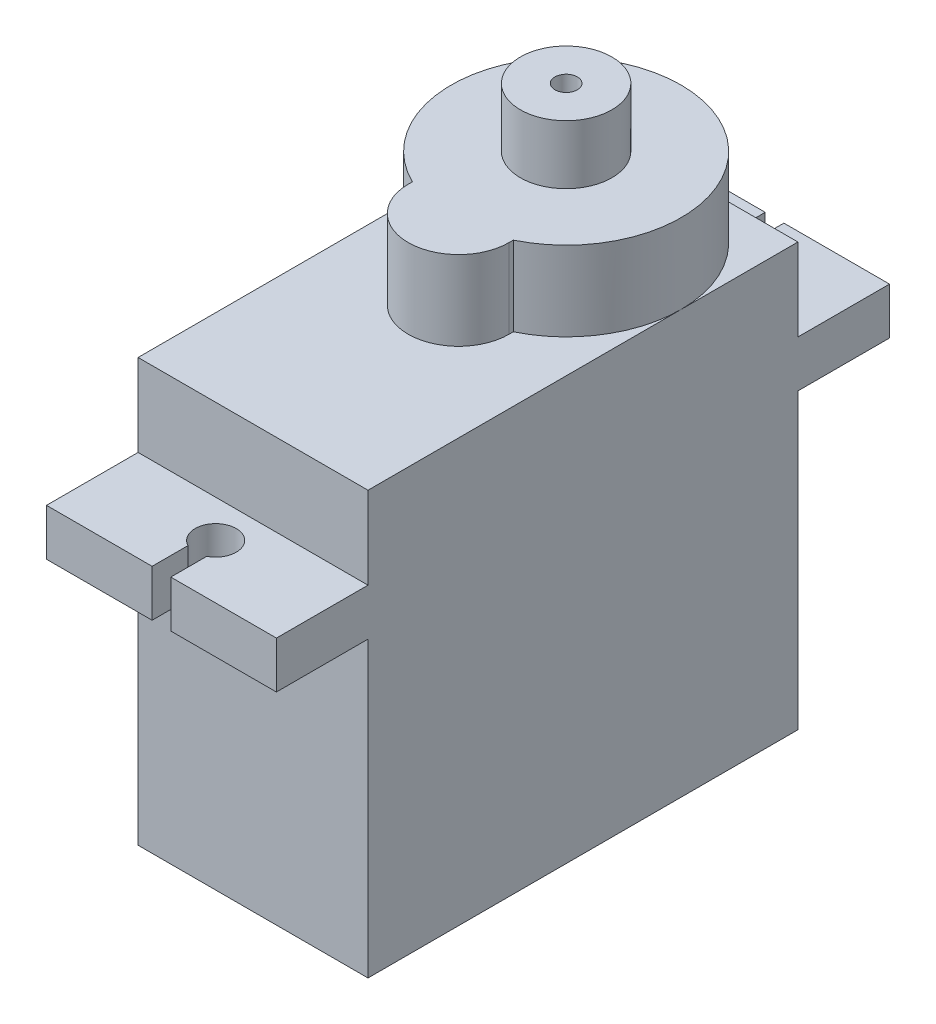
SolidWorks part; units mm, degrees
ref_plane "Ön Düzlem" through (0, 0, 0) normal (0, 0, 1) x (1, 0, 0)
ref_plane "Üst Düzlem" through (0, 0, 0) normal (0, 1, 0) x (1, 0, 0)
ref_plane "Sağ Düzlem" through (0, 0, 0) normal (1, 0, 0) x (0, 0, -1)
sketch "Çizim1" plane through (0, 0, 0) normal (0, 1, 0) x (1, 0, 0)
  line L1 (-6.15, -11.5) -> (6.15, -11.5)
  line L2 (-6.15, -11.5) -> (-6.15, 11.5)
  line L3 (-6.15, 11.5) -> (6.15, 11.5)
  line L4 (6.15, -11.5) -> (6.15, 11.5)
  line L5 (-6.15, -11.5) -> (6.15, 11.5) construction
  line L6 (-6.15, 11.5) -> (6.15, -11.5) construction
  point P0 (0, 0)
  dimension "D1" = 12.3
  dimension "D2" = 23
extrude "Yükseklik-Ekstrüzyon1" add sketch "Çizim1" along normal blind 22.6
ref_plane "Düzlem1" through (0, 18.2, 0) normal (0, 1, 0) x (1, 0, 0)
sketch "Çizim2" plane through (0, 18.2, 0) normal (0, 1, 0) x (1, 0, 0)
  line L0 (6.15, -11.5) -> (6.15, 11.5) construction
  line L1 (-6.15, -16.4) -> (6.15, -16.4)
  line L2 (-6.15, -16.4) -> (-6.15, 16.4)
  line L3 (-6.15, 16.4) -> (6.15, 16.4)
  line L4 (6.15, -16.4) -> (6.15, 16.4)
  line L5 (-6.15, -16.4) -> (6.15, 16.4) construction
  line L6 (-6.15, 16.4) -> (6.15, -16.4) construction
  line L7 (0, 13.5) -> (0, 16.4) construction
  line L8 (0.5, 14.4798) -> (0.5, 16.4)
  line L9 (-0.5, 14.4798) -> (-0.5, 16.4)
  line L10 (-0.5, 16.4) -> (0.5, 16.4)
  line L11 (-6.15, 0) -> (6.15, 0) construction
  line L12 (0.5, -14.4798) -> (0.5, -16.4)
  line L13 (-0.5, -14.4798) -> (-0.5, -16.4)
  line L14 (6.15, 11.5) -> (-6.15, 11.5) construction
  circle A0 centre (0, 13.5) radius 1.1
  circle A1 centre (0, -13.5) radius 1.1
  point P0 (0, 0)
  dimension "D2" = 2.2
  dimension "D1" = 32.8
  dimension "D3" = 2
  dimension "D4" = 0.5
extrude "Yükseklik-Ekstrüzyon2" add sketch "Çizim2" against normal blind 2.5 contours L13 A1 L12 L1 L4 L3 L8 A0 L9 L2
ref_plane "Düzlem2" through (0, 4.8, 0) normal (0, -1, 0) x (-1, 0, 0)
sketch "Çizim3" plane through (0, 4.8, 0) normal (0, -1, 0) x (-1, 0, 0)
  line L0 (-1.8, 11.5) -> (1.8, 11.5)
  line L1 (-1.8, 11.5) -> (-1.8, 14.5)
  line L2 (1.8, 11.5) -> (1.8, 14.5)
  line L3 (-1.8, 14.5) -> (1.8, 14.5)
  line L4 (-6.15, 11.5) -> (6.15, 11.5) construction
  line L5 (-6.15, 11.5) -> (6.15, 11.5) construction
  point P8 (0, 11.5)
  dimension "D1" = 3.6
  dimension "D2" = 3
extrude "Yükseklik-Ekstrüzyon3" add sketch "Çizim3" along normal blind 1.2
sketch "Çizim4" plane through (0, 22.6, 0) normal (0, 1, 0) x (1, 0, 0)
  line L0 (-6.15, 11.5) -> (-6.15, -11.5) construction
  line L2 (6.15, -11.5) -> (6.15, 11.5) construction
  line L3 (6.15, 11.5) -> (-6.15, 11.5) construction
  line L4 (-2.7, -0.5) -> (-2.7, -0.2756)
  line L5 (2.7, -0.5) -> (2.7, -0.2756)
  circle A0 centre (0, 5.25) radius 6.15
  arc A1 (-2.7, -0.5) -> (2.7, -0.5) centre (0, -0.5) ccw
  point P2 (0, 11.4)
  point P8 (0, 11.5)
  point P15 (0, -3.2)
  dimension "D2" = 2.7
  dimension "D1" = 0.1
  dimension "D3" = 14.6
extrude "Yükseklik-Ekstrüzyon4" add sketch "Çizim4" along normal blind 4.25 contours A0 | L4 A1 L5 A0
sketch "Çizim5" plane through (0, 26.85, 0) normal (0, 1, 0) x (1, 0, 0)
  circle A0 centre (0, 5.25) radius 0.6
  arc A1 (6.15, 5.25) -> (-6.15, 5.25) centre (0, 5.25) ccw construction
  circle A2 centre (0, 5.25) radius 2.45
  arc A3 (2.7, -0.2756) -> (-2.7, -0.2756) centre (0, 5.25) ccw construction
  dimension "D1" = 1.2
  dimension "D2" = 4.9
ref_plane "Düzlem3" through (0, 30, 0) normal (0, 1, 0) x (1, 0, 0)
extrude "Yükseklik-Ekstrüzyon6" add sketch "Çizim5" along normal up to surface (3.15 mm away) up to plane "Düzlem3"
sketch "Çizim6" plane through (0, 0, -14.5) normal (0, 0, -1) x (-1, 0, 0)
  line L0 (-1.8, 3.6) -> (1.8, 3.6) construction
  line L1 (-0.6667, 3.6) -> (-0.5667, 3.6)
  line L2 (-0.6667, 3.6) -> (-0.6667, 4.8)
  line L3 (-0.6667, 4.8) -> (-0.5667, 4.8)
  line L4 (-0.5667, 3.6) -> (-0.5667, 4.8)
  line L5 (1.8, 4.8) -> (-1.8, 4.8) construction
  line L6 (-0.6667, 4.2) -> (-1.8, 4.2) construction
  line L7 (0.5667, 4.8) -> (0.6667, 4.8)
  line L8 (0.5667, 4.8) -> (0.5667, 3.6)
  line L9 (0.5667, 3.6) -> (0.6667, 3.6)
  line L10 (0.6667, 4.8) -> (0.6667, 3.6)
  line L11 (-1.8, 3.6) -> (-1.8, 4.8) construction
  line L12 (-0.5667, 4.2) -> (0.5667, 4.2) construction
  line L13 (0.6667, 4.2) -> (1.8, 4.2) construction
  line L14 (1.8, 3.6) -> (1.8, 4.8) construction
  dimension "D1" = 0.1
  dimension "D2" = 0.1
extrude "Kes-Ekstrüzyon1" cut sketch "Çizim6" against normal up to surface (3 mm away) up to face at (0, 7.85, -11.5)
fillet "Radyus1" radius 0.5 12 edges at (-0.6667, 4.8, -13) (-1.8, 4.8, -13) (-1.8, 3.6, -13) (-0.6667, 3.6, -13) (0.5667, 3.6, -13) (-0.5667, 3.6, -13) (-0.5667, 4.8, -13) (0.5667, 4.8, -13) (1.8, 3.6, -13) (0.6667, 4.8, -13) (0.6667, 3.6, -13) (1.8, 4.8, -13)
